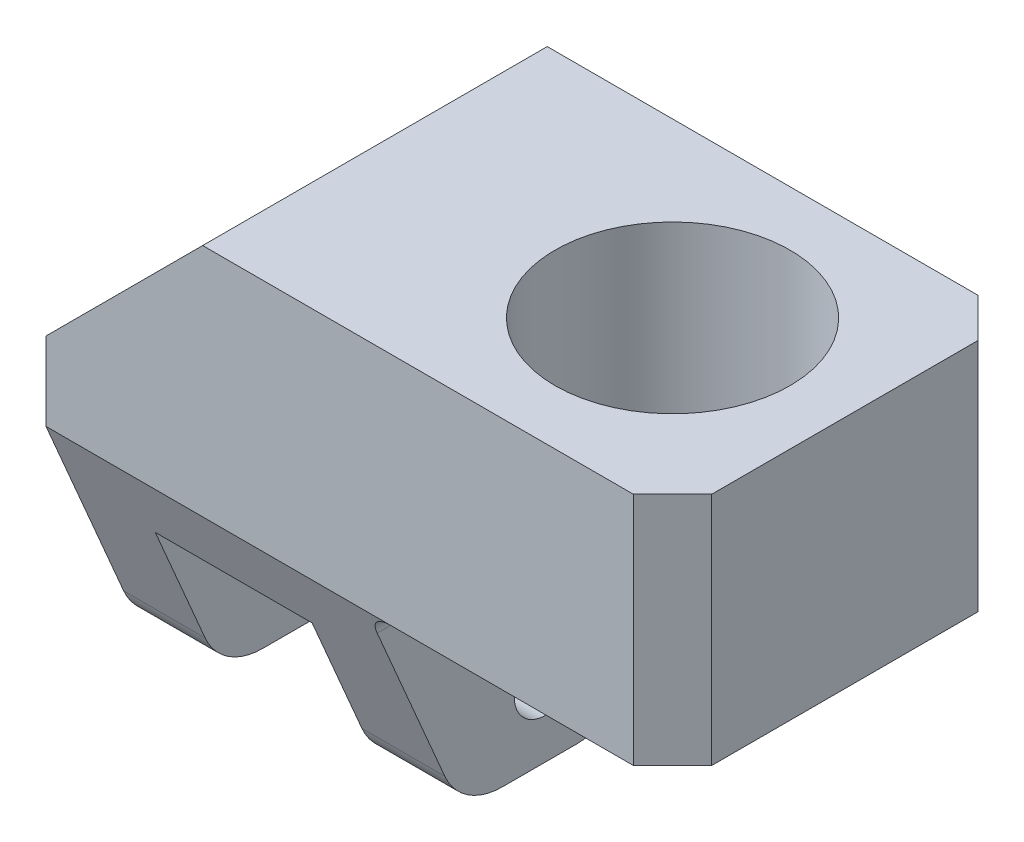
SolidWorks part; units mm, degrees
ref_plane "Спереди" through (0, 0, 0) normal (0, 0, 1) x (1, 0, 0)
ref_plane "Сверху" through (0, 0, 0) normal (0, 1, 0) x (1, 0, 0)
ref_plane "Справа" through (0, 0, 0) normal (1, 0, 0) x (0, 0, -1)
sketch "Эскиз1" plane through (0, 0, 0) normal (0, 1, 0) x (1, 0, 0)
  line L0 (0, 0) -> (66.7996, 0) construction
  line L1 (-58, 22) -> (22, 22)
  line L2 (-58, 22) -> (-58, -22)
  line L3 (-58, -22) -> (22, -22)
  line L4 (22, 22) -> (22, -22)
  line L5 (0, 0) -> (0, 51.1408) construction
  circle A0 centre (0, 0) radius 15
  dimension "D1" = 22
  dimension "D2" = 22
  dimension "D3" = 22
  dimension "D4" = 58
extrude "Вытянуть1" add sketch "Эскиз1" along normal blind 30
chamfer "Фаска1" distance 20 angle 45 1 edges at (-58, 30, 0)
sketch "Эскиз2" plane through (0, 0, 0) normal (0, -1, 0) x (1, 0, 0)
  line L0 (22, -22) -> (-58, -22) construction
  line L1 (-58, 22) -> (-17, 22)
  line L2 (-58, 22) -> (-58, -22)
  line L3 (-58, -22) -> (-17, -22)
  line L4 (-17, 22) -> (-17, -22)
extrude "Вытянуть2" add sketch "Эскиз2" along normal blind 28
sketch "Эскиз3" plane through (-58, 0, 0) normal (-1, 0, 0) x (0, 0, 1)
  circle A0 centre (-0.7887, -18.8413) radius 4
extrude "Вырез-Вытянуть1" cut sketch "Эскиз3" against normal through all
sketch "Эскиз4" plane through (0, 0, 22) normal (0, 0, 1) x (1, 0, 0)
  line L1 (-47.6091, -28) -> (-27.5791, -28)
  line L2 (-47.6091, -28) -> (-47.6091, -8.2987)
  line L3 (-47.6091, -8.2987) -> (-27.5791, -8.2987)
  line L4 (-27.5791, -28) -> (-27.5791, -8.2987)
extrude "Вырез-Вытянуть2" cut sketch "Эскиз4" against normal through all
chamfer "Фаска4" distance 5 angle 45 2 edges at (22, 15, -22) (22, 15, 22)
fillet "Скругление1" radius 3 1 edges
sketch "Эскиз5" plane through (-58, 0, 0) normal (-1, 0, 0) x (0, 0, 1)
  line L0 (-22, 0) -> (-10, -28)
  line L1 (22, -28) -> (-22, -28) construction
  line L2 (-22, 10) -> (-22, -28) construction
  line L3 (0, 0) -> (0, 20.0898) construction
  line L4 (-22, 0) -> (-22, -28)
  line L5 (-22, -28) -> (-10, -28)
  line L6 (22, -28) -> (10, -28)
  line L7 (22, 0) -> (10, -28)
  line L8 (22, 0) -> (22, -28)
extrude "Вырез-Вытянуть3" cut sketch "Эскиз5" against normal through all
fillet "Скругление2" radius 8 4 edges at (-22.2895, -28, -10) (-52.8045, -28, -10) (-22.2895, -28, 10) (-52.8045, -28, 10)
